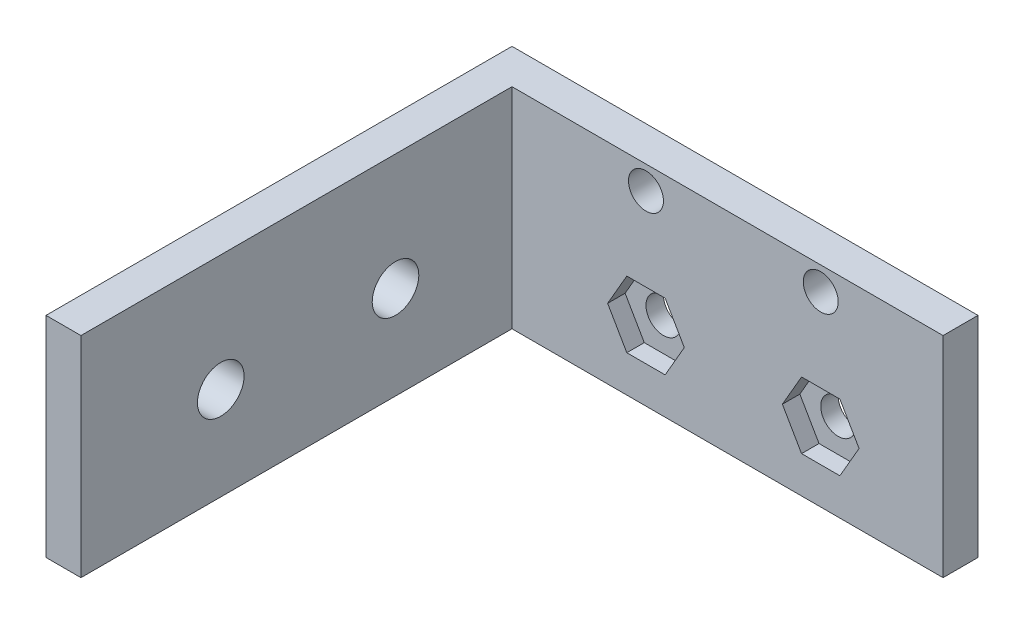
SolidWorks part; units mm, degrees
ref_plane "Plan de face" through (0, 0, 0) normal (0, 0, 1) x (1, 0, 0)
ref_plane "Plan de dessus" through (0, 0, 0) normal (0, 1, 0) x (1, 0, 0)
ref_plane "Plan de droite" through (0, 0, 0) normal (1, 0, 0) x (0, 0, -1)
sketch "Esquisse1" plane through (0, 0, 0) normal (0, 0, 1) x (1, 0, 0)
  line L1 (0, 0) -> (40, 0)
  line L2 (0, 0) -> (0, 18)
  line L3 (0, 18) -> (40, 18)
  line L4 (40, 0) -> (40, 18)
  dimension "D1" = 18
  dimension "D2" = 40
extrude "Boss.-Extru.1" add sketch "Esquisse1" along normal blind 3
sketch "Esquisse2" plane through (0, 0, 3) normal (0, 0, 1) x (1, 0, 0)
  line L0 (0, 0) -> (40, 0) construction
  line L1 (0, 18) -> (3, 18)
  line L2 (0, 18) -> (0, 0)
  line L3 (0, 0) -> (3, 0)
  line L4 (3, 18) -> (3, 0)
  dimension "D1" = 3
extrude "Boss.-Extru.2" add sketch "Esquisse2" along normal blind 37
sketch "Esquisse3" plane through (0, 0, 3) normal (0, 0, 1) x (1, 0, 0)
  line L0 (3, 0) -> (3, 18) construction
  line L4 (3, 0) -> (40, 0) construction
  circle A0 centre (14.5, 16) radius 1.5
  circle A1 centre (29.5, 16) radius 1.5
  circle A2 centre (14.5, 6) radius 1.5
  circle A3 centre (29.5, 6) radius 1.5
  dimension "D2" = 3
  dimension "D3" = 3
  dimension "D4" = 3
  dimension "D5" = 15
  dimension "D1" = 3
  dimension "D6" = 10
  dimension "D7" = 11.5
  dimension "D8" = 11.5
  dimension "D9" = 10
  dimension "D10" = 15
  dimension "D11" = 6
  dimension "D12" = 6
extrude "Enlèv. mat.-Extru.1" cut sketch "Esquisse3" against normal through all
sketch "Esquisse4" plane through (3, 0, 0) normal (1, 0, 0) x (0, 0, -1)
  line L0 (-40, 18) -> (-3, 18) construction
  line L1 (-3, 0) -> (-3, 18) construction
  circle A0 centre (-28, 8) radius 2
  circle A1 centre (-13, 8) radius 2
  dimension "D1" = 4
  dimension "D2" = 4
  dimension "D3" = 15
  dimension "D4" = 10
  dimension "D5" = 10
  dimension "D6" = 10
extrude "Enlèv. mat.-Extru.2" cut sketch "Esquisse4" against normal through all
sketch "Esquisse5" plane through (0, 0, 3) normal (0, 0, 1) x (1, 0, 0)
  line L0 (3, 0) -> (40, 0) construction
  line L1 (16.1454, 8.85) -> (12.8546, 8.85)
  line L2 (12.8546, 8.85) -> (11.2091, 6)
  line L3 (11.2091, 6) -> (12.8546, 3.15)
  line L4 (12.8546, 3.15) -> (16.1454, 3.15)
  line L5 (16.1454, 3.15) -> (17.7909, 6)
  line L6 (17.7909, 6) -> (16.1454, 8.85)
  line L7 (31.1454, 8.85) -> (27.8546, 8.85)
  line L8 (27.8546, 8.85) -> (26.2091, 6)
  line L9 (26.2091, 6) -> (27.8546, 3.15)
  line L10 (27.8546, 3.15) -> (31.1454, 3.15)
  line L11 (31.1454, 3.15) -> (32.7909, 6)
  line L12 (32.7909, 6) -> (31.1454, 8.85)
  circle A0 centre (14.5, 6) radius 2.85 construction
  circle A1 centre (29.5, 6) radius 2.85 construction
  point P10 (29.5, 3.15)
  point P19 (14.5, 3.15)
  dimension "D1" = 5.7
  dimension "D2" = 5.7
extrude "Enlèv. mat.-Extru.3" cut sketch "Esquisse5" against normal blind 1.5
